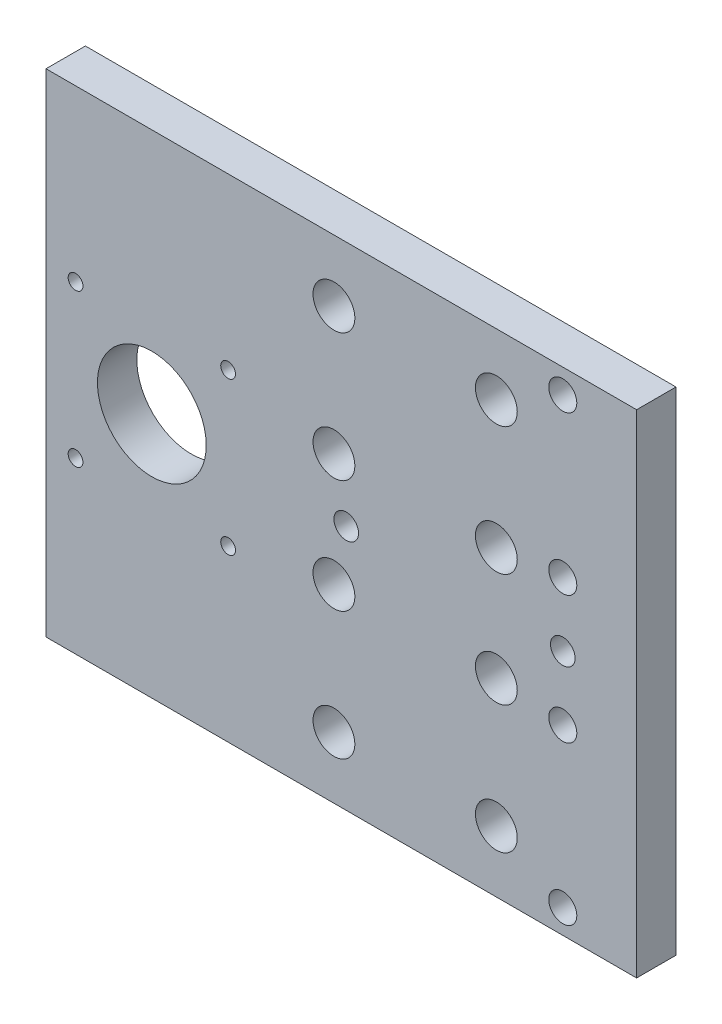
SolidWorks part; units mm, degrees
ref_plane "Ön Düzlem" through (0, 0, 0) normal (0, 0, 1) x (1, 0, 0)
ref_plane "Üst Düzlem" through (0, 0, 0) normal (0, 1, 0) x (1, 0, 0)
ref_plane "Sağ Düzlem" through (0, 0, 0) normal (1, 0, 0) x (0, 0, -1)
sketch "Sketch1" plane through (0, 0, 0) normal (0, 0, 1) x (1, 0, 0)
  line L0 (0, -60) -> (0, 60)
  line L1 (0, 60) -> (-120, 60)
  line L2 (-120, 60) -> (-120, -60)
  line L3 (-120, -60) -> (0, -60)
  line L4 (-45, 24.5) -> (-45, -24.5) construction
  line L5 (-114, -15.5) -> (-83, -15.5) construction
  line L6 (-114, -15.5) -> (-114, 15.5) construction
  line L7 (-114, 15.5) -> (-83, 15.5) construction
  line L8 (-83, -15.5) -> (-83, 15.5) construction
  line L9 (-114, -15.5) -> (-83, 15.5) construction
  line L10 (-114, 15.5) -> (-83, -15.5) construction
  line L11 (-61.5, 11.5) -> (-28.5, 11.5) construction
  line L12 (-61.5, 11.5) -> (-61.5, 37.5) construction
  line L13 (-61.5, 37.5) -> (-28.5, 37.5) construction
  line L14 (-28.5, 11.5) -> (-28.5, 37.5) construction
  line L15 (-61.5, 11.5) -> (-28.5, 37.5) construction
  line L16 (-61.5, 37.5) -> (-28.5, 11.5) construction
  line L17 (-61.5, -37.5) -> (-28.5, -37.5) construction
  line L18 (-61.5, -37.5) -> (-61.5, -11.5) construction
  line L19 (-61.5, -11.5) -> (-28.5, -11.5) construction
  line L20 (-28.5, -37.5) -> (-28.5, -11.5) construction
  line L21 (-61.5, -37.5) -> (-28.5, -11.5) construction
  line L22 (-61.5, -11.5) -> (-28.5, -37.5) construction
  line L25 (-15, 45.1) -> (-15, 13) construction
  line L26 (-15, -13) -> (-15, -45.1) construction
  line L27 (-15, 29.05) -> (-15, -29.05) construction
  circle A0 centre (-98.5, 0) radius 11.05
  circle A1 centre (-83, 15.5) radius 1.5
  circle A2 centre (-114, 15.5) radius 1.5
  circle A3 centre (-114, -15.5) radius 1.5
  circle A4 centre (-83, -15.5) radius 1.5
  circle A5 centre (-61.5, 37.5) radius 2.5
  circle A6 centre (-28.5, 37.5) radius 2.5
  circle A7 centre (-61.5, 11.5) radius 2.5
  circle A8 centre (-28.5, 11.5) radius 2.5
  circle A9 centre (-61.5, -11.5) radius 2.5
  circle A10 centre (-28.5, -11.5) radius 2.5
  circle A11 centre (-28.5, -37.5) radius 2.5
  circle A12 centre (-61.5, -37.5) radius 2.5
  circle A13 centre (-15, 45.1) radius 2.85
  circle A14 centre (-15, 13) radius 2.85
  circle A15 centre (-15, -13) radius 2.85
  circle A16 centre (-15, -45.1) radius 2.85
  point P0 (-120, -60)
  point P4 (0, 0)
  point P6 (-120, 60)
  point P16 (-45, -24.5)
  point P19 (-45, 24.5)
  point P29 (-45, 0)
  point P51 (-15, 0)
  dimension "D3" = 22.1
  dimension "D5" = 3
  dimension "D6" = 6
  dimension "D11" = 5
  dimension "D13" = 5.7
  dimension "D16" = 15
  dimension "D1" = 120
  dimension "D2" = 120
  dimension "D4" = 31
  dimension "D7" = 33
  dimension "D8" = 26
  dimension "D9" = 23
  dimension "D10" = 45
  dimension "D12" = 32.1
  dimension "D17" = 26
extrude "Boss-Extrude1" add sketch "Sketch1" along normal blind 8
sketch "Sketch3" plane through (0, 0, 8) normal (0, 0, 1) x (1, 0, 0)
  line L0 (0, 60) -> (-120, 60) construction
  line L1 (-139.9411, 69.037) -> (29.9987, 69.037)
  line L2 (-139.9411, 69.037) -> (-139.9411, 50)
  line L3 (-139.9411, 50) -> (29.9987, 50)
  line L4 (29.9987, 69.037) -> (29.9987, 50)
  line L5 (-139.9411, -50) -> (48.8035, -50)
  line L6 (-139.9411, -50) -> (-139.9411, -79.2519)
  line L7 (-139.9411, -79.2519) -> (48.8035, -79.2519)
  line L8 (48.8035, -50) -> (48.8035, -79.2519)
  line L9 (-120, -60) -> (0, -60) construction
  dimension "D1" = 10
  dimension "D2" = 10
extrude "Cut-Extrude1" cut sketch "Sketch3" against normal blind 10
sketch "Sketch4" plane through (0, 0, 8) normal (0, 0, 1) x (1, 0, 0)
  circle A0 centre (-61.5, 37.5) radius 4.25
  circle A1 centre (-28.5, 37.5) radius 4.25
  circle A2 centre (-61.5, 11.5) radius 4.25
  circle A3 centre (-28.5, 11.5) radius 4.25
  circle A4 centre (-61.5, -11.5) radius 4.25
  circle A5 centre (-28.5, -11.5) radius 4.25
  circle A6 centre (-61.5, -37.5) radius 4.25
  circle A7 centre (-28.5, -37.5) radius 4.25
  dimension "D1" = 8.5
extrude "Cut-Extrude2" cut sketch "Sketch4" against normal blind 6
sketch "Sketch5" plane through (0, 0, 8) normal (0, 0, 1) x (1, 0, 0)
  line L0 (-67, 19.3524) -> (-67, -23.041) construction
  line L1 (0, -50) -> (0, 50) construction
  line L2 (-15, 0) -> (-59, 0) construction
  circle A0 centre (-15, 0) radius 2.5
  circle A1 centre (-59, 0) radius 2.5
  point P9 (0, 0)
  dimension "D1" = 5
  dimension "D3" = 15
  dimension "D2" = 67
  dimension "D4" = 8
extrude "Cut-Extrude3" cut sketch "Sketch5" against normal through all
